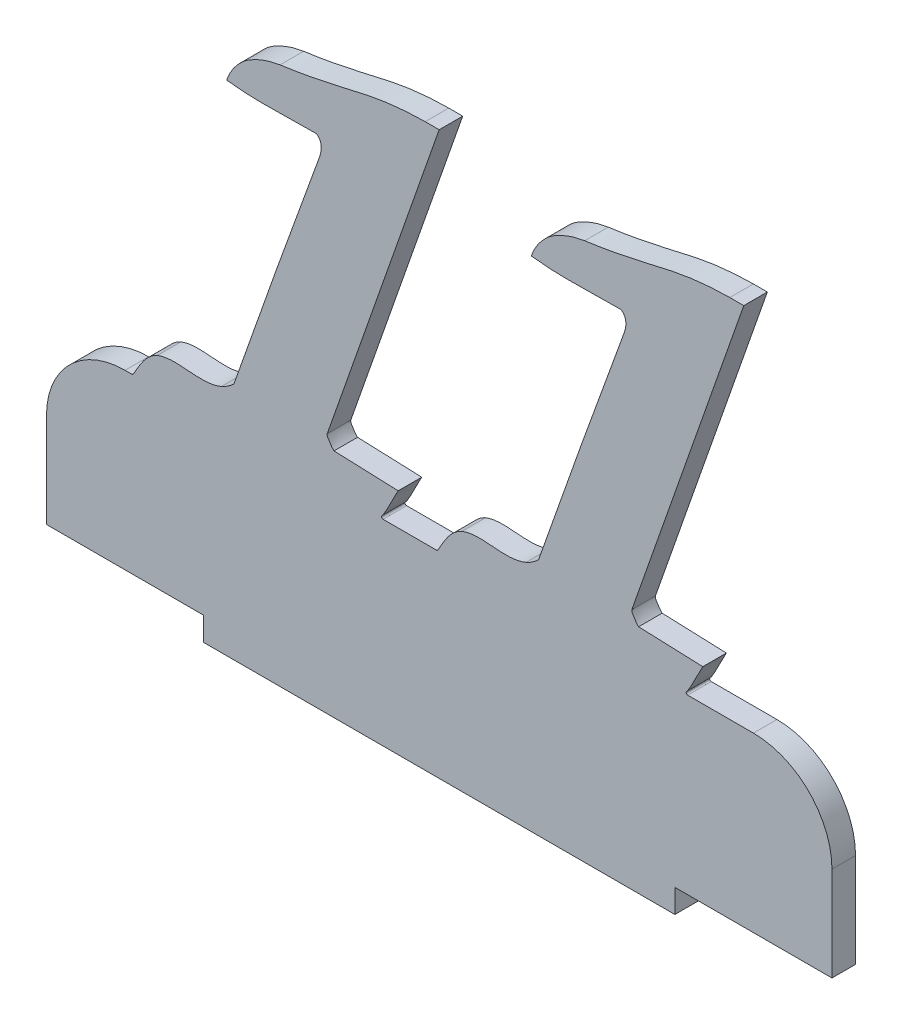
SolidWorks part; units mm, degrees
ref_plane "Front Plane" through (0, 0, 0) normal (0, 0, 1) x (1, 0, 0)
ref_plane "Top Plane" through (0, 0, 0) normal (0, 1, 0) x (1, 0, 0)
ref_plane "Right Plane" through (0, 0, 0) normal (1, 0, 0) x (0, 0, -1)
sketch "Sketch1" plane through (0, 0, 0) normal (0, 0, 1) x (1, 0, 0)
  line L0 (0, 20) -> (100, 20) construction
  line L1 (42.3587, 22) -> (49.7724, 22)
  line L2 (0, 22) -> (0, 0)
  line L3 (0, 0) -> (20, 0)
  line L4 (100, 22) -> (100, 0)
  line L5 (0, 22) -> (10.9921, 22)
  line L6 (81.139, 22) -> (100, 22)
  line L7 (49.9934, 68.5192) -> (35.744, 27.8819)
  line L8 (36.604, 26.4159) -> (44.7745, 26.1032)
  line L10 (88.7737, 68.5192) -> (74.5243, 27.8819)
  line L11 (80, 0) -> (100, 0)
  line L12 (75.3843, 26.4159) -> (83.5548, 26.1032)
  line L13 (20, 0) -> (20, -3)
  line L14 (20, -3) -> (80, -3)
  line L15 (80, 0) -> (80, -3)
  spline S0 degree 3 poles (44.7745, 26.1032) (44.1795, 25.09) (43.6344, 23.7677) (42.7937, 22.3951) (42.4822, 22.1014) (42.3587, 22) knots 0 0 0 0 0.504343 0.619768 0.688442 0.688442 0.688442 0.688442
  spline S1 degree 3 poles (10.9921, 22) (11.06, 22.1164) (11.3749, 22.6662) (12.1706, 24.0936) (13.1652, 25.2632) (14.106, 25.6927) knots 0.181428 0.181428 0.181428 0.181428 0.248912 0.498933 1 1 1 1
  spline S2 degree 3 poles (14.106, 25.6927) (15.4474, 26.212) (18.1981, 25.9372) (20.9674, 25.7816) (22.2764, 26.3573) knots 0 0 0 0 0.501452 1 1 1 1
  spline S3 degree 2 poles (22.2764, 26.3573) (23.158, 26.7478) (23.8597, 27.4128) knots 0 0 0 1 1 1
  spline S4 degree 3 poles (23.8597, 27.4128) (25.642, 32.448) (29.167, 42.5708) (32.856, 52.635) (34.6885, 57.6904) knots 0 0 0 0 0.498323 1 1 1 1
  spline S5 degree 3 poles (34.6885, 57.6904) (34.8717, 58.1879) (35.1668, 59.1545) (34.7142, 60.0659) (34.3562, 60.2705) knots 0 0 0 0 0.581397 1 1 1 1
  spline S6 degree 3 poles (34.3562, 60.2705) (32.4395, 60.3043) (28.6345, 60.1204) (24.8215, 60.2251) (22.941, 60.466) knots 0 0 0 0 0.503015 1 1 1 1
  spline S7 degree 3 poles (22.941, 60.466) (23.173, 61.1332) (23.6572, 62.0821) (24.5752, 63.1428) (25.3485, 63.8654) (26.2965, 64.4191) (27.7235, 65.1018) (28.9155, 65.4166) (29.7432, 65.5481) knots 0 0 0 0 0.237267 0.352024 0.469659 0.590381 0.718477 1 1 1 1
  spline S8 degree 3 poles (29.7432, 65.5481) (32.8555, 65.9465) (36.7172, 66.7985) (41.339, 67.8783) (44.4189, 68.3608) (46.712, 68.5084) (48.2147, 68.5192) knots 0 0 0 0 0.501478 0.63281 0.759518 1 1 1 1
  spline S9 degree 3 poles (48.2147, 68.5192) (48.4232, 68.5192) (49.0161, 68.5192) (49.609, 68.5192) (49.9934, 68.5192) knots 0 0 0 0 0.351648 1 1 1 1
  spline S10 degree 3 poles (35.744, 27.8819) (35.6908, 27.6821) (36.0224, 27.1724) (36.3001, 26.6897) (36.604, 26.4159) knots 0 0 0 0 0.324502 1 1 1 1
  spline S11 degree 3 poles (83.5548, 26.1032) (82.9598, 25.09) (82.4147, 23.7677) (81.574, 22.3951) (81.2625, 22.1014) (81.139, 22) knots 0 0 0 0 0.504343 0.619768 0.688442 0.688442 0.688442 0.688442
  spline S12 degree 3 poles (49.7724, 22) (49.8403, 22.1164) (50.1552, 22.6662) (50.9509, 24.0936) (51.9455, 25.2632) (52.8863, 25.6927) knots 0.181428 0.181428 0.181428 0.181428 0.248912 0.498933 1 1 1 1
  spline S13 degree 3 poles (52.8863, 25.6927) (54.2277, 26.212) (56.9784, 25.9372) (59.7477, 25.7816) (61.0567, 26.3573) knots 0 0 0 0 0.501452 1 1 1 1
  spline S14 degree 2 poles (61.0567, 26.3573) (61.9383, 26.7478) (62.64, 27.4128) knots 0 0 0 1 1 1
  spline S15 degree 3 poles (62.64, 27.4128) (64.4223, 32.448) (67.9473, 42.5708) (71.6363, 52.635) (73.4688, 57.6904) knots 0 0 0 0 0.498323 1 1 1 1
  spline S16 degree 3 poles (73.4688, 57.6904) (73.652, 58.1879) (73.9471, 59.1545) (73.4945, 60.0659) (73.1365, 60.2705) knots 0 0 0 0 0.581397 1 1 1 1
  spline S17 degree 3 poles (73.1365, 60.2705) (71.2198, 60.3043) (67.4148, 60.1204) (63.6018, 60.2251) (61.7213, 60.466) knots 0 0 0 0 0.503015 1 1 1 1
  spline S18 degree 3 poles (61.7213, 60.466) (61.9533, 61.1332) (62.4375, 62.0821) (63.3555, 63.1428) (64.1288, 63.8654) (65.0768, 64.4191) (66.5038, 65.1018) (67.6958, 65.4166) (68.5235, 65.5481) knots 0 0 0 0 0.237267 0.352024 0.469659 0.590381 0.718477 1 1 1 1
  spline S19 degree 3 poles (68.5235, 65.5481) (71.6358, 65.9465) (75.4975, 66.7985) (80.1193, 67.8783) (83.1992, 68.3608) (85.4923, 68.5084) (86.995, 68.5192) knots 0 0 0 0 0.501478 0.63281 0.759518 1 1 1 1
  spline S20 degree 3 poles (86.995, 68.5192) (87.2035, 68.5192) (87.7964, 68.5192) (88.3893, 68.5192) (88.7737, 68.5192) knots 0 0 0 0 0.351648 1 1 1 1
  spline S21 degree 3 poles (74.5243, 27.8819) (74.4711, 27.6821) (74.8027, 27.1724) (75.0804, 26.6897) (75.3843, 26.4159) knots 0 0 0 0 0.324502 1 1 1 1
  dimension "D1" = 100
  dimension "D2" = 3
  dimension "D3" = 20
  dimension "D4" = 20
  dimension "D5" = 20
extrude "Boss-Extrude1" add sketch "Sketch1" along normal blind 3
fillet "Fillet1" radius 10 2 edges at (0, 22, 1.5) (100, 22, 1.5)
fillet "Fillet2" radius 0.2 4 edges at (49.7724, 22, 1.5) (81.139, 22, 1.5) (42.3587, 22, 1.5) (10.9921, 22, 1.5)
